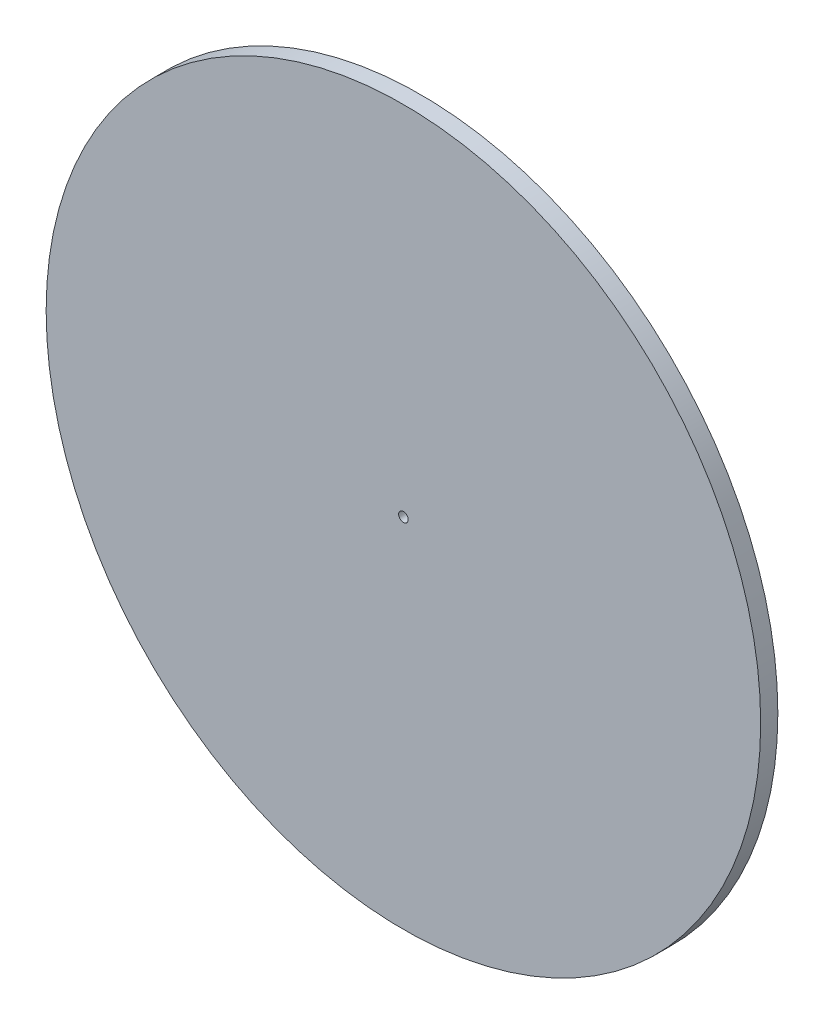
SolidWorks part; units mm, degrees
ref_plane "Front Plane" through (0, 0, 0) normal (0, 0, 1) x (1, 0, 0)
ref_plane "Top Plane" through (0, 0, 0) normal (0, 1, 0) x (1, 0, 0)
ref_plane "Right Plane" through (0, 0, 0) normal (1, 0, 0) x (0, 0, -1)
sketch "Sketch1" plane through (0, 0, 0) normal (0, 0, 1) x (1, 0, 0)
  circle A0 centre (0, 0) radius 750
  circle A1 centre (0, 0) radius 10
  dimension "D1" = 1500
  dimension "D2" = 20
extrude "Boss-Extrude1" add sketch "Sketch1" along normal mid plane 36
